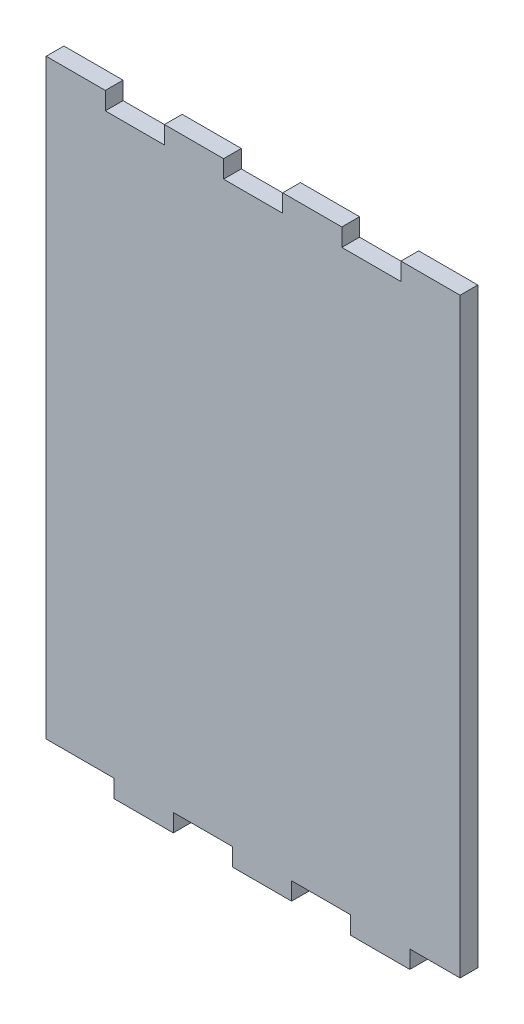
SolidWorks part; units mm, degrees
ref_plane "Front Plane" through (0, 0, 0) normal (0, 0, 1) x (1, 0, 0)
ref_plane "Top Plane" through (0, 0, 0) normal (0, 1, 0) x (1, 0, 0)
ref_plane "Right Plane" through (0, 0, 0) normal (1, 0, 0) x (0, 0, -1)
sketch "Sketch1" plane through (0, 0, 0) normal (0, 0, 1) x (1, 0, 0)
  line L1 (-35, -50) -> (35, -50)
  line L2 (-35, -50) -> (-35, 50)
  line L3 (-35, 50) -> (35, 50)
  line L4 (35, -50) -> (35, 50)
  line L5 (-35, -50) -> (35, 50) construction
  line L6 (-35, 50) -> (35, -50) construction
  line L7 (-3.5, -50) -> (6.5, -50)
  line L8 (-3.5, -50) -> (-3.5, -53)
  line L9 (-3.5, -53) -> (6.5, -53)
  line L10 (6.5, -50) -> (6.5, -53)
  line L11 (-3.5, -50) -> (6.5, -53) construction
  line L12 (-3.5, -53) -> (6.5, -50) construction
  line L13 (16.5, -50) -> (26.5, -50)
  line L14 (16.5, -50) -> (16.5, -53)
  line L15 (16.5, -53) -> (26.5, -53)
  line L16 (26.5, -50) -> (26.5, -53)
  line L17 (16.5, -50) -> (26.5, -53) construction
  line L18 (16.5, -53) -> (26.5, -50) construction
  line L19 (-13.5, -50) -> (-23.5, -50)
  line L20 (-13.5, -50) -> (-13.5, -53)
  line L21 (-13.5, -53) -> (-23.5, -53)
  line L22 (-23.5, -50) -> (-23.5, -53)
  line L23 (-13.5, -50) -> (-23.5, -53) construction
  line L24 (-13.5, -53) -> (-23.5, -50) construction
  point P0 (0, 0)
  point P10 (1.5, -51.5)
  point P15 (21.5, -51.5)
  point P20 (-18.5, -51.5)
  dimension "D1" = 10
  dimension "D2" = 10
  dimension "D3" = 10
  dimension "D4" = 3
  dimension "D5" = 3
  dimension "D6" = 3
  dimension "D7" = 10
  dimension "D8" = 10
  dimension "D9" = 70
  dimension "D10" = 100
  dimension "D11" = 11.5
extrude "Boss-Extrude1" add sketch "Sketch1" along normal blind 3 contours L1 L4 L3 L2 | L16 L1 L14 L15 | L10 L1 L8 L9 | L1 L22 L21 L20
sketch "Sketch2" plane through (0, 0, 3) normal (0, 0, 1) x (1, 0, 0)
  line L0 (-35, 50) -> (-25, 50) construction
  line L1 (-35, 50) -> (35, 50) construction
  line L3 (-25, 50) -> (-15, 50)
  line L4 (-25, 50) -> (-25, 47)
  line L5 (-25, 47) -> (-15, 47)
  line L6 (-15, 50) -> (-15, 47)
  line L7 (-25, 50) -> (-15, 47) construction
  line L8 (-25, 47) -> (-15, 50) construction
  line L9 (-5, 50) -> (5, 50)
  line L10 (-5, 50) -> (-5, 47)
  line L11 (-5, 47) -> (5, 47)
  line L12 (5, 50) -> (5, 47)
  line L13 (-5, 50) -> (5, 47) construction
  line L14 (-5, 47) -> (5, 50) construction
  line L15 (15, 50) -> (25, 50)
  line L16 (15, 50) -> (15, 47)
  line L17 (15, 47) -> (25, 47)
  line L18 (25, 50) -> (25, 47)
  line L19 (15, 50) -> (25, 47) construction
  line L20 (15, 47) -> (25, 50) construction
  point P8 (-20, 48.5)
  point P14 (0, 48.5)
  point P18 (20, 48.5)
  point P19 (15, 48.5)
  dimension "D1" = 10
  dimension "D2" = 3
  dimension "D3" = 3
  dimension "D4" = 3
  dimension "D5" = 10
  dimension "D6" = 10
  dimension "D7" = 10
  dimension "D8" = 10
extrude "Cut-Extrude1" cut sketch "Sketch2" against normal through all
